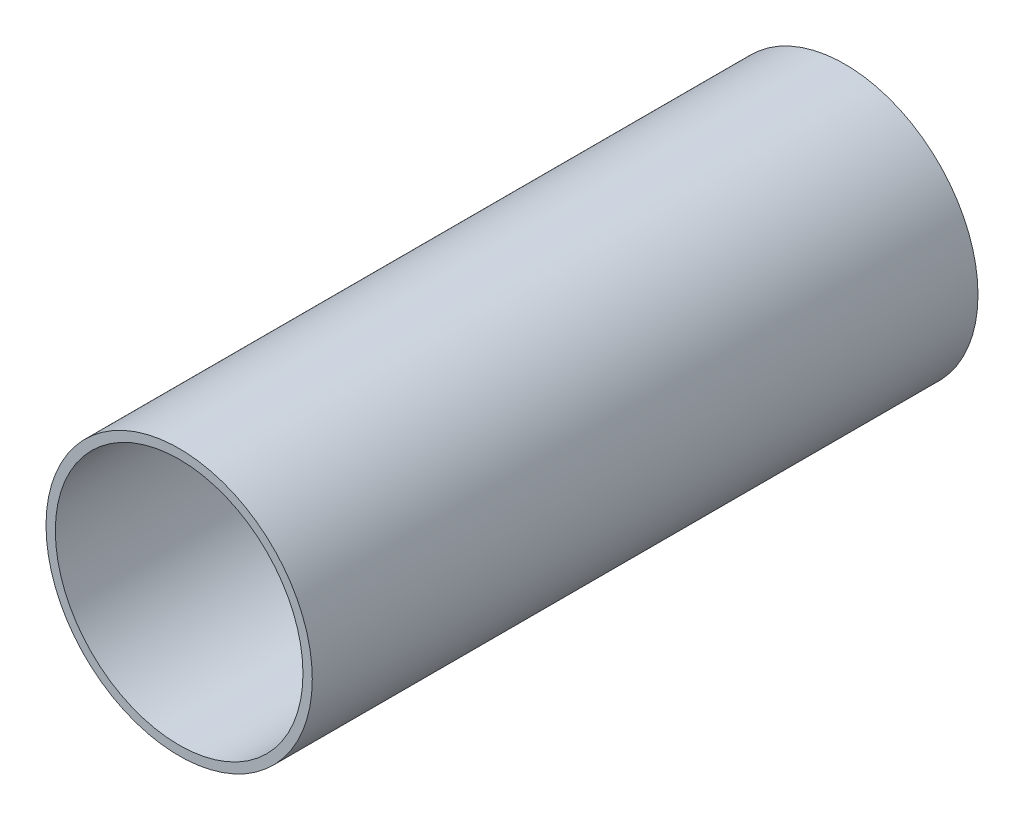
SolidWorks part; units mm, degrees
ref_plane "Front Plane" through (0, 0, 0) normal (0, 0, 1) x (1, 0, 0)
ref_plane "Top Plane" through (0, 0, 0) normal (0, 1, 0) x (1, 0, 0)
ref_plane "Right Plane" through (0, 0, 0) normal (1, 0, 0) x (0, 0, -1)
sketch "Sketch1" plane through (0, 0, 0) normal (0, 0, 1) x (1, 0, 0)
  circle A0 centre (0, 0) radius 11.811
  circle A1 centre (0, 0) radius 12.7
  dimension "D1" = 23.622
  dimension "D2" = 25.4
extrude "Boss-Extrude1" add sketch "Sketch1" along normal mid plane 63.5
